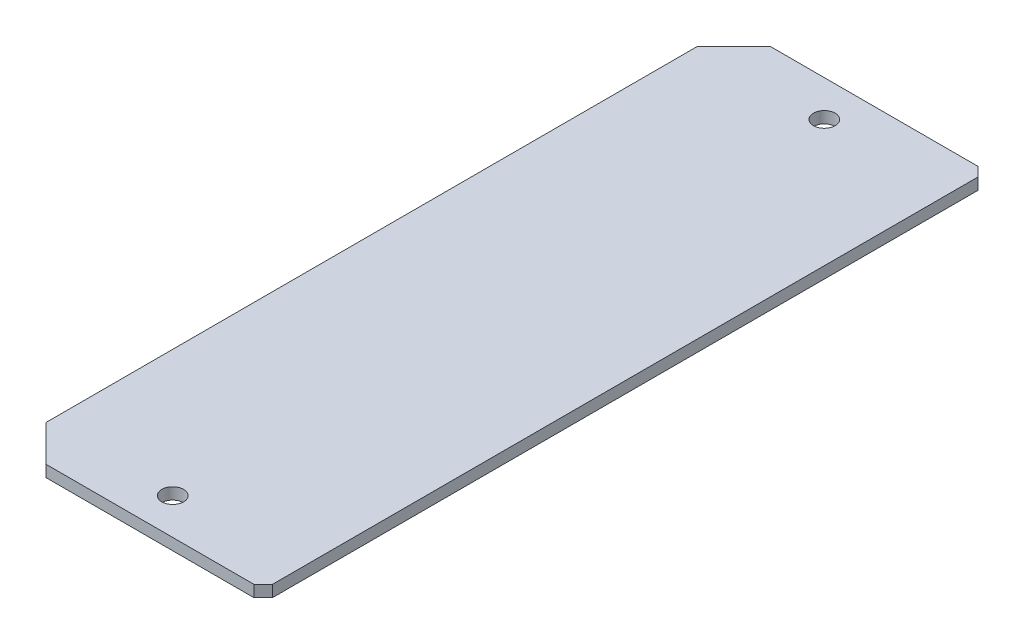
SolidWorks part; units mm, degrees
ref_plane "Front Plane" through (0, 0, 0) normal (0, 0, 1) x (1, 0, 0)
ref_plane "Top Plane" through (0, 0, 0) normal (0, 1, 0) x (1, 0, 0)
ref_plane "Right Plane" through (0, 0, 0) normal (1, 0, 0) x (0, 0, -1)
sketch "Sketch1" plane through (0, 0, 0) normal (0, 1, 0) x (1, 0, 0)
  line L1 (-17.5, 50) -> (17.5, 50)
  line L2 (-17.5, 50) -> (-17.5, -50)
  line L3 (-17.5, -50) -> (17.5, -50)
  line L4 (17.5, 50) -> (17.5, -50)
  line L5 (-17.5, 50) -> (17.5, -50) construction
  line L6 (-17.5, -50) -> (17.5, 50) construction
  point P0 (0, 0)
  dimension "D1" = 35
  dimension "D2" = 100
extrude "Boss-Extrude1" add sketch "Sketch1" along normal blind 1.6
chamfer "Chamfer1" distance 5 angle 45 2 edges at (-17.5, 0.8, -50) (-17.5, 0.8, 50)
chamfer "Chamfer2" distance 1.27 angle 45 2 edges at (17.5, 0.8, 50) (17.5, 0.8, -50)
sketch "Sketch2" plane through (0, 1.6, 0) normal (0, 1, 0) x (-1, 0, 0)
  line L0 (-16.23, -50) -> (12.5, -50) construction
  line L1 (12.5, 50) -> (-16.23, 50) construction
  circle A0 centre (0, -45) radius 1.5
  circle A1 centre (0, 45) radius 1.5
  dimension "D1" = 3
  dimension "D2" = 3
  dimension "D3" = 5
  dimension "D4" = 5
extrude "Cut-Extrude1" cut sketch "Sketch2" against normal blind 10
